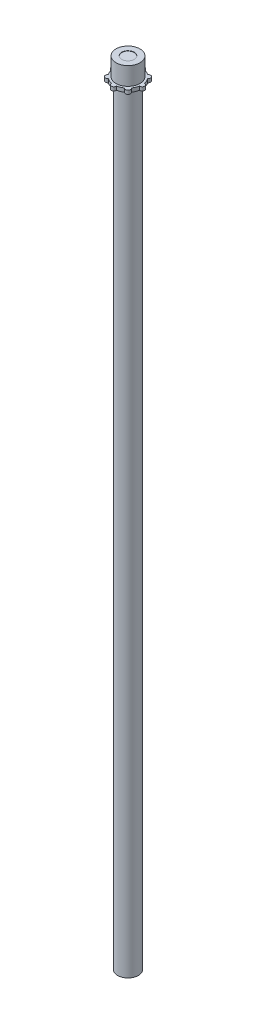
SolidWorks part; units mm, degrees
material "Alloy Steel"
ref_plane "Front" through (0, 0, 0) normal (0, 0, 1) x (1, 0, 0)
ref_plane "Top" through (0, 0, 0) normal (0, 1, 0) x (1, 0, 0)
ref_plane "Right" through (0, 0, 0) normal (1, 0, 0) x (0, 0, -1)
sketch "Sketch2" plane through (0, 0, 0) normal (0, 1, 0) x (1, 0, 0)
  circle A0 centre (0, 0) radius 7.874
  dimension "D1" = 15.748
extrude "Boss-Extrude1" add sketch "Sketch2" along normal blind 586.74
sketch "Sketch3" plane through (0, 586.74, 0) normal (0, 1, 0) x (1, 0, 0)
  arc A0 (-8.8561, 6.1726) -> (-10.6269, 1.8976) centre (0, 0) ccw
  arc A2 (1.8976, 10.6269) -> (-1.8976, 10.6269) centre (0, 10.795) ccw
  arc A3 (8.8561, 6.1726) -> (6.1726, 8.8561) centre (7.6332, 7.6332) ccw
  arc A4 (10.6269, -1.8976) -> (10.6269, 1.8976) centre (10.795, 0) ccw
  arc A5 (6.1726, -8.8561) -> (8.8561, -6.1726) centre (7.6332, -7.6332) ccw
  arc A6 (-1.8976, -10.6269) -> (1.8976, -10.6269) centre (0, -10.795) ccw
  arc A7 (-8.8561, -6.1726) -> (-6.1726, -8.8561) centre (-7.6332, -7.6332) ccw
  arc A8 (-10.6269, 1.8976) -> (-10.6269, -1.8976) centre (-10.795, 0) ccw
  arc A9 (-6.1726, 8.8561) -> (-8.8561, 6.1726) centre (-7.6332, 7.6332) ccw
  arc A10 (-1.8976, 10.6269) -> (-6.1726, 8.8561) centre (0, 0) ccw
  arc A11 (6.1726, 8.8561) -> (1.8976, 10.6269) centre (0, 0) ccw
  arc A12 (10.6269, 1.8976) -> (8.8561, 6.1726) centre (0, 0) ccw
  arc A13 (8.8561, -6.1726) -> (10.6269, -1.8976) centre (0, 0) ccw
  arc A14 (1.8976, -10.6269) -> (6.1726, -8.8561) centre (0, 0) ccw
  arc A15 (-6.1726, -8.8561) -> (-1.8976, -10.6269) centre (0, 0) ccw
  arc A16 (-10.6269, -1.8976) -> (-8.8561, -6.1726) centre (0, 0) ccw
  point P21 (0, 0)
  dimension "D1" = 8
  dimension "D2" = 10.795
  dimension "D3" = 1.905
extrude "Boss-Extrude3" add sketch "Sketch3" along normal blind 2.794
sketch "Sketch4" plane through (0, 589.534, 0) normal (0, 1, 0) x (1, 0, 0)
  circle A0 centre (0, 0) radius 9.144
extrude "Boss-Extrude4" add sketch "Sketch4" along normal blind 13.716
sketch "Sketch6" plane through (0, 603.25, 0) normal (0, 1, 0) x (1, 0, 0)
  circle A0 centre (0, 0) radius 4.7625
extrude "Cut-Extrude1" cut sketch "Sketch6" against normal blind 0.254
